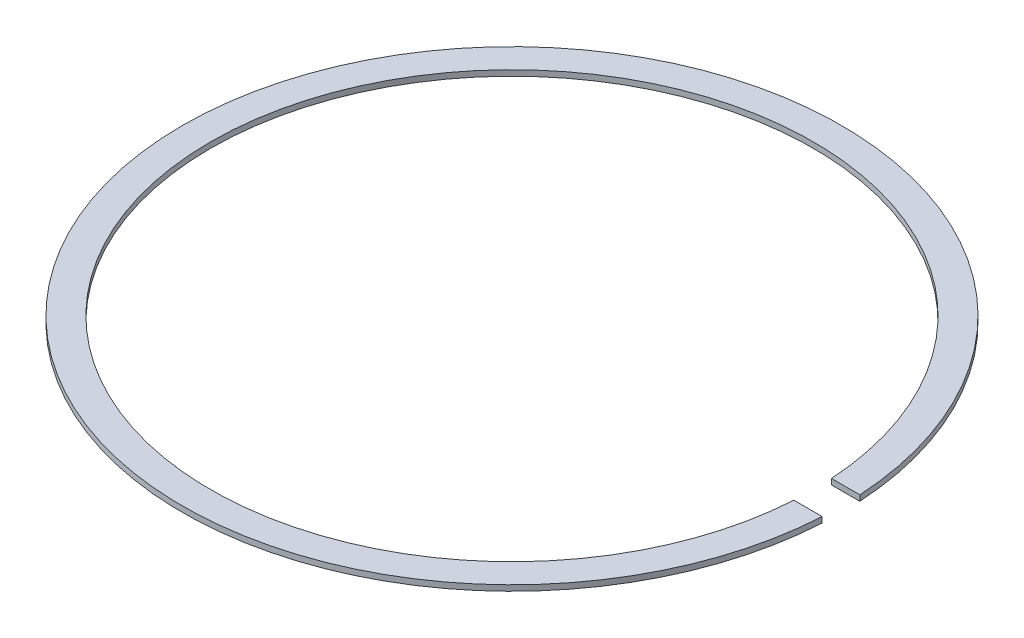
SolidWorks part; units mm, degrees
ref_plane "Front Plane" through (0, 0, 0) normal (0, 0, 1) x (1, 0, 0)
ref_plane "Top Plane" through (0, 0, 0) normal (0, 1, 0) x (1, 0, 0)
ref_plane "Right Plane" through (0, 0, 0) normal (1, 0, 0) x (0, 0, -1)
sketch "Sketch1" plane through (0, 0, 0) normal (0, 1, 0) x (1, 0, 0)
  line L0 (-160, 0) -> (160, 0) construction
  circle A0 centre (0, 0) radius 160
  circle A1 centre (0, 0) radius 175
  dimension "D1" = 320
  dimension "D2" = 350
extrude "Boss-Extrude1" add sketch "Sketch1" along normal mid plane 3
sketch "Sketch2" plane through (0, 0, 0) normal (0, 1, 0) x (1, 0, 0)
  line L0 (-175, 0) -> (175, 0) construction
  line L1 (0, 175) -> (0, -175) construction
  line L3 (183.8046, 10) -> (151.1954, 10)
  line L4 (183.8046, 10) -> (183.8046, -10)
  line L5 (183.8046, -10) -> (151.1954, -10)
  line L6 (151.1954, 10) -> (151.1954, -10)
  line L7 (183.8046, 10) -> (151.1954, -10) construction
  line L8 (183.8046, -10) -> (151.1954, 10) construction
  circle A0 centre (0, 0) radius 175 construction
  circle A1 centre (0, 0) radius 167.5 construction
  circle A2 centre (0, 0) radius 160 construction
  point P7 (167.5, 0)
  point P14 (0, 0)
  point P18 (183.8046, 10)
  dimension "D2" = 7.5
  dimension "D1" = 20
extrude "axis gap" cut sketch "Sketch2" against normal through all both and the other way through all
